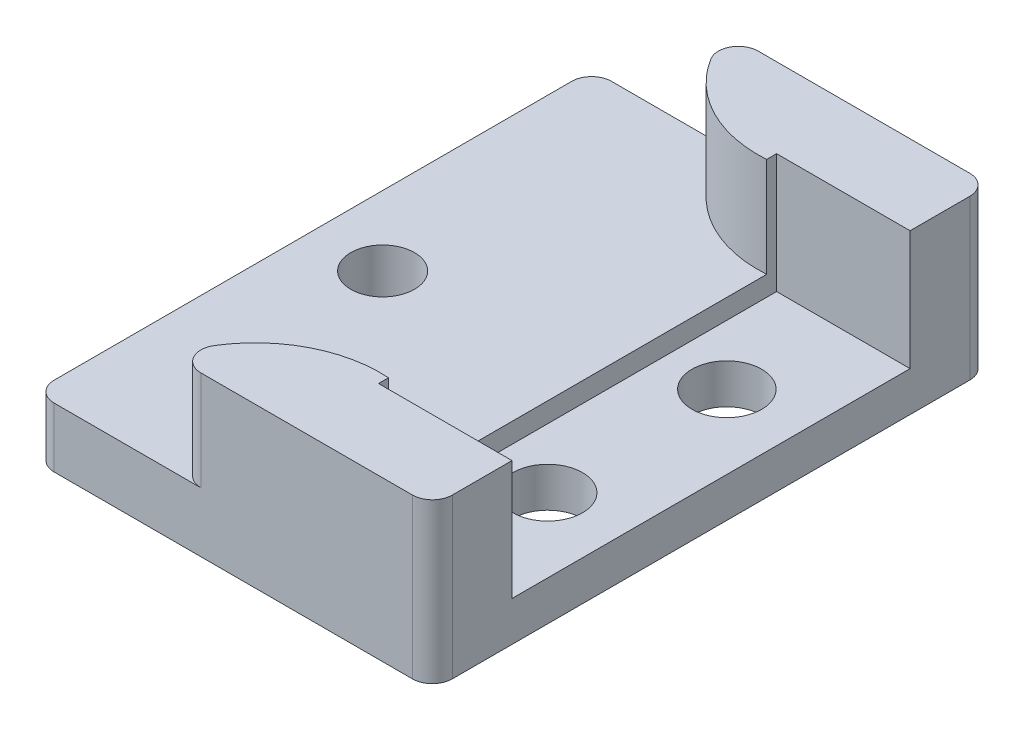
SolidWorks part; units mm, degrees
ref_plane "Alzado" through (0, 0, 0) normal (0, 0, 1) x (1, 0, 0)
ref_plane "Planta" through (0, 0, 0) normal (0, 1, 0) x (1, 0, 0)
ref_plane "Vista lateral" through (0, 0, 0) normal (1, 0, 0) x (0, 0, -1)
sketch "Croquis2" plane through (0, 0, 0) normal (0, 1, 0) x (1, 0, 0)
  line L1 (-10.8434, 8.4739) -> (9.1566, 8.4739)
  line L2 (-10.8434, 8.4739) -> (-10.8434, -19.5261)
  line L3 (-10.8434, -19.5261) -> (9.1566, -19.5261)
  line L4 (9.1566, 8.4739) -> (9.1566, -19.5261)
  dimension "D1" = 20
  dimension "D2" = 28
extrude "Saliente-Extruir1" add sketch "Croquis2" along normal blind 8
sketch "Croquis3" plane through (0, 8, 0) normal (0, 1, 0) x (1, 0, 0)
  line L0 (9.1566, 4.4739) -> (1.1799, 4.4739) construction
  line L1 (9.1566, -19.5261) -> (9.1566, 8.4739) construction
  line L2 (9.1566, -15.5261) -> (5.7192, -15.5261) construction
  line L5 (9.1566, 8.4739) -> (-10.8434, 8.4739) construction
  line L6 (9.1566, 4.4739) -> (2.4509, 4.4739)
  line L7 (9.1566, 4.4739) -> (9.1566, -15.5261)
  line L8 (9.1566, -15.5261) -> (2.4509, -15.5261)
  line L9 (2.4509, 4.4739) -> (2.4509, -15.5261)
  point P6 (0, 0)
  point P7 (0, 0)
  dimension "D1" = 20
  dimension "D2" = 4
extrude "Cortar-Extruir1" cut sketch "Croquis3" against normal blind 6
sketch "Croquis5" plane through (0, 8, 0) normal (0, 1, 0) x (1, 0, 0)
  line L0 (2.4509, 4.4739) -> (-1.2584, 4.9739) construction
  line L1 (2.4509, -15.5261) -> (0, -8.0261) construction
  line L2 (2.4509, 4.4739) -> (2.4509, -15.5261) construction
  line L3 (2.4509, 3.9739) -> (1.59, 3.9739)
  line L4 (2.4509, 3.9739) -> (2.4509, -15.0261)
  line L5 (2.4509, -15.0261) -> (1.59, -15.0261)
  line L7 (-10.8434, 8.4739) -> (9.1566, -19.5261) construction
  line L8 (-0.8434, -5.5261) -> (2.4509, -5.5261) construction
  line L9 (9.1566, 8.4739) -> (-10.8434, 8.4739) construction
  arc A0 (2.4509, 3.9739) -> (-4.0017, 8.4739) centre (2.0204, 10.2329) cw
  arc A1 (2.4509, -15.0261) -> (-4.0017, -19.5261) centre (2.0204, -21.2851) ccw
  line M7 (2.4509, -15.5261) -> (2.4509, 4.4739)
  line M10 (9.1566, 8.4739) -> (-10.8434, 8.4739)
  line M11 (-10.8434, 8.4739) -> (-10.8434, -19.5261)
  line M12 (-10.8434, -19.5261) -> (9.1566, -19.5261)
  dimension "D2" = 19
extrude "Cortar-Extruir2" cut sketch "Croquis5" against normal blind 5 contours A1 A0 M7 M10 M11 M12
sketch "Croquis6" plane through (0, 3, 0) normal (0, 1, 0) x (1, 0, 0)
  line L0 (-7.3434, 8.4739) -> (-7.3434, -19.5261) construction
  line L1 (-4.0017, 8.4739) -> (-10.8434, 8.4739) construction
  line L2 (-10.8434, -19.5261) -> (-4.0017, -19.5261) construction
  line L3 (-10.8434, 8.4739) -> (-10.8434, -19.5261) construction
  circle A0 centre (-7.3434, -5.5261) radius 1.6
  dimension "D2" = 3.2
  dimension "D1" = 3.5
extrude "Cortar-Extruir3" cut sketch "Croquis6" against normal blind 3
fillet "Redondeo1" radius 1 6 edges at (-4.0017, 5.5, -8.4739) (-4.0017, 5.5, 19.5261) (9.1566, 4, -8.4739) (-10.8434, 1.5, -8.4739) (-10.8434, 1.5, 19.5261) (9.1566, 4, 19.5261)
sketch "Sketch1" plane through (0, 2, 0) normal (0, 1, 0) x (1, 0, 0)
  line L0 (9.1566, 4.4739) -> (2.4509, 4.4739) construction
  line L4 (2.4509, 4.4739) -> (2.4509, -15.5261) construction
  circle A0 centre (5.4509, -1.0261) radius 1.75
  circle A1 centre (5.4509, -10.0261) radius 1.75
  point P4 (0, 0)
  point P5 (0, 0)
  dimension "D1" = 9
  dimension "D2" = 3.5
  dimension "D3" = 3.5
  dimension "D4" = 5.5
  dimension "D5" = 3
extrude "Cut-Extrude1" cut sketch "Sketch1" against normal through all
